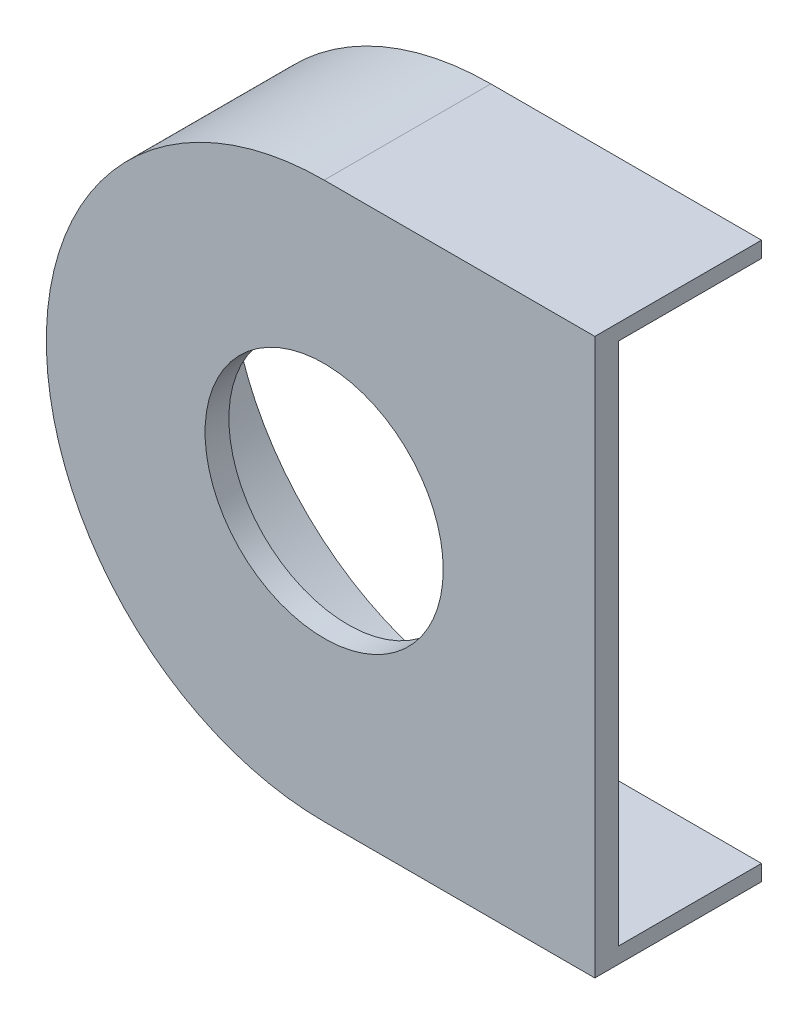
SolidWorks part; units mm, degrees
ref_plane "Piano frontale" through (0, 0, 0) normal (0, 0, 1) x (1, 0, 0)
ref_plane "Piano superiore" through (0, 0, 0) normal (0, 1, 0) x (1, 0, 0)
ref_plane "Piano destro" through (0, 0, 0) normal (1, 0, 0) x (0, 0, -1)
sketch "Schizzo1" plane through (0, 0, 0) normal (0, 0, 1) x (1, 0, 0)
  line L1 (17.05, -17.5) -> (0, -17.5)
  line L2 (17.05, -17.5) -> (17.05, 17.5)
  line L3 (17.05, 17.5) -> (0, 17.5)
  line L5 (17.05, -17.5) -> (-12.2122, 12.5345) construction
  line L6 (17.05, 17.5) -> (-12.2122, -12.5345) construction
  arc A0 (0, 17.5) -> (0, -17.5) centre (0, 0) ccw
  circle A1 centre (0, 0) radius 7.5
  dimension "D1" = 35
  dimension "D3" = 15
  dimension "D2" = 17.05
extrude "Estrusione-Estrusione1" add sketch "Schizzo1" along normal blind 1.5
sketch "Schizzo2" plane through (0, 0, 0) normal (0, 0, -1) x (-1, 0, 0)
  line L0 (-17.05, 17.5) -> (0, 17.5) construction
  line L1 (0, -17.5) -> (-17.05, -17.5) construction
  line L2 (-17.05, 17.5) -> (0, 17.5)
  line L3 (0, -17.5) -> (-17.05, -17.5)
  line L4 (-17.05, 16.5) -> (0, 16.5)
  line L5 (0, -16.5) -> (-17.05, -16.5)
  line L6 (-17.05, -16.5) -> (-17.05, -17.5)
  line L7 (-17.05, 17.5) -> (-17.05, 16.5)
  arc A0 (0, -17.5) -> (0, 17.5) centre (0, 0) ccw construction
  arc A1 (0, -17.5) -> (0, 17.5) centre (0, 0) ccw
  arc A2 (0, -16.5) -> (0, 16.5) centre (0, 0) ccw
  dimension "D1" = 1
extrude "Estrusione-Estrusione2" add sketch "Schizzo2" along normal blind 9
